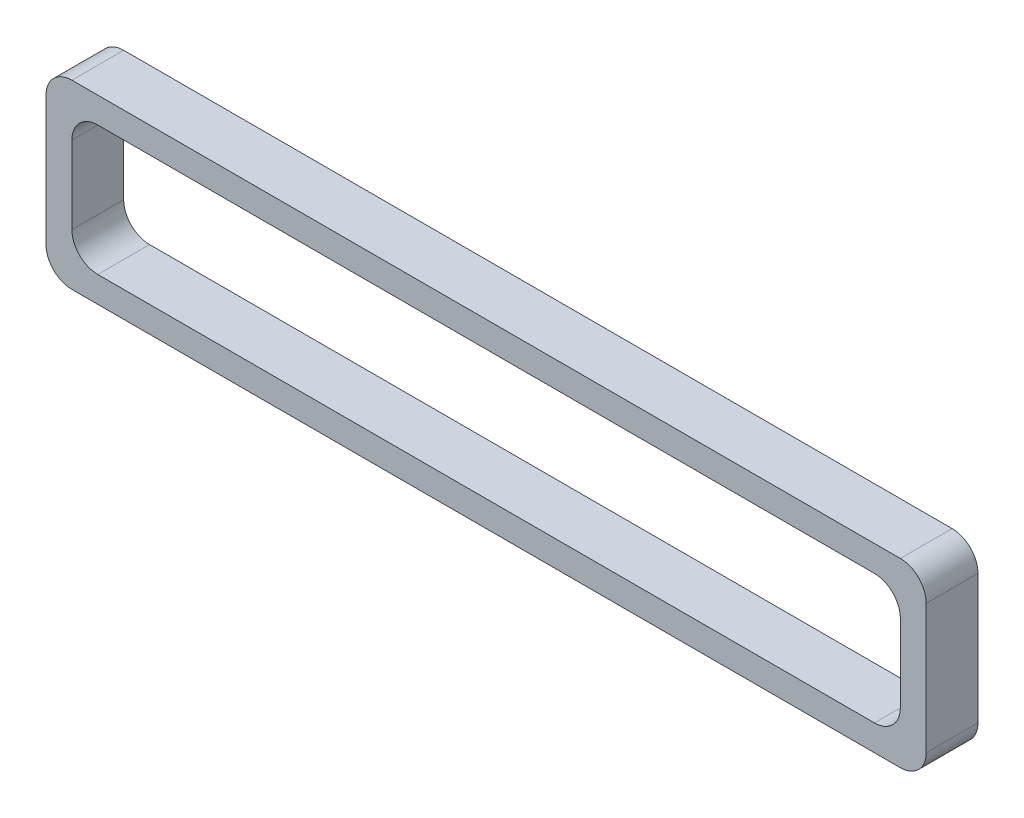
SolidWorks part; units mm, degrees
ref_plane "Front Plane" through (0, 0, 0) normal (0, 0, 1) x (1, 0, 0)
ref_plane "Top Plane" through (0, 0, 0) normal (0, 1, 0) x (1, 0, 0)
ref_plane "Right Plane" through (0, 0, 0) normal (1, 0, 0) x (0, 0, -1)
sketch "Sketch1" plane through (0, 0, 0) normal (0, 0, 1) x (1, 0, 0)
  line L1 (-15, 2.5) -> (15, 2.5)
  line L2 (-16, 1.5) -> (-16, -1.5)
  line L3 (-15, -2.5) -> (15, -2.5)
  line L4 (16, 1.5) -> (16, -1.5)
  line L5 (-16, 2.5) -> (16, -2.5) construction
  line L6 (-16, -2.5) -> (16, 2.5) construction
  line L7 (-16, 3.5) -> (16, 3.5)
  line L8 (-17, 2.5) -> (-17, -2.5)
  line L9 (-16, -3.5) -> (16, -3.5)
  line L10 (17, 2.5) -> (17, -2.5)
  line L11 (-17, 3.5) -> (17, -3.5) construction
  line L12 (-17, -3.5) -> (17, 3.5) construction
  arc A0 (16, -3.5) -> (17, -2.5) centre (16, -2.5) ccw
  arc A1 (-17, -2.5) -> (-16, -3.5) centre (-16, -2.5) ccw
  arc A2 (-16, 3.5) -> (-17, 2.5) centre (-16, 2.5) ccw
  arc A3 (16, 3.5) -> (17, 2.5) centre (16, 2.5) cw
  arc A4 (15, 2.5) -> (16, 1.5) centre (15, 1.5) cw
  arc A5 (15, -2.5) -> (16, -1.5) centre (15, -1.5) ccw
  arc A6 (-16, -1.5) -> (-15, -2.5) centre (-15, -1.5) ccw
  arc A7 (-15, 2.5) -> (-16, 1.5) centre (-15, 1.5) ccw
  point P0 (0, 0)
  point P6 (0, 0)
  dimension "D1" = 1
  dimension "D2" = 30
  dimension "D3" = 1
  dimension "D4" = 1
  dimension "D5" = 3
extrude "Boss-Extrude1" add sketch "Sketch1" along normal blind 2
